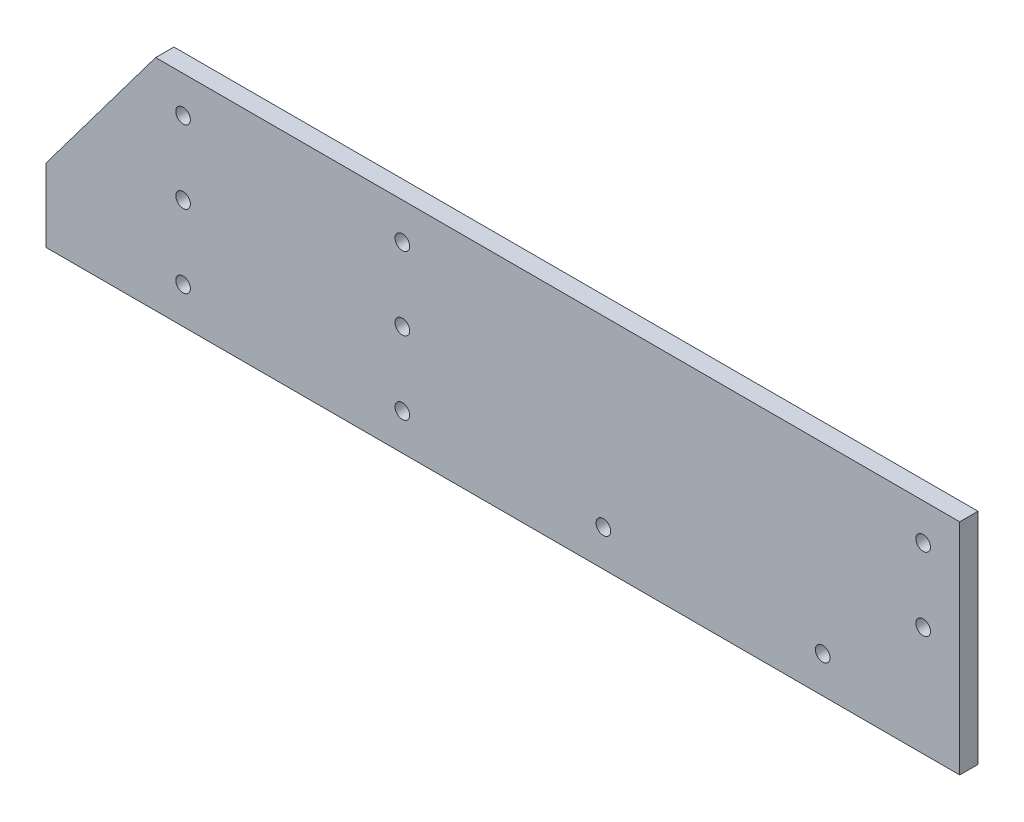
SolidWorks part; units mm, degrees
ref_plane "Front" through (0, 0, 0) normal (0, 0, 1) x (1, 0, 0)
ref_plane "Top" through (0, 0, 0) normal (0, 1, 0) x (1, 0, 0)
ref_plane "Right" through (0, 0, 0) normal (1, 0, 0) x (0, 0, -1)
sketch "Esquisse1" plane through (0, 0, 0) normal (0, 0, 1) x (1, 0, 0)
  line L1 (0, 0) -> (250, 0)
  line L2 (0, 0) -> (0, 60)
  line L3 (0, 60) -> (250, 60)
  line L4 (250, 0) -> (250, 60)
  dimension "D1" = 250
  dimension "D2" = 60
extrude "Boss.-Extru.1" add sketch "Esquisse1" along normal blind 5
sketch "Esquisse2" plane through (0, 0, 5) normal (0, 0, 1) x (1, 0, 0)
  line L0 (125, 0) -> (125, 60) construction
  line L1 (0, 0) -> (250, 0) construction
  line L2 (250, 60) -> (0, 60) construction
  line L3 (0, 10) -> (250, 10) construction
  line L4 (0, 60) -> (0, 0) construction
  line L5 (250, 0) -> (250, 60) construction
  line L6 (240, 60) -> (240, 50) construction
  line L7 (240, 50) -> (240, 30) construction
  line L8 (37.5, 10) -> (37.5, 60) construction
  line L9 (97.5, 10) -> (97.5, 60) construction
  line L10 (37.5, 35) -> (97.5, 35) construction
  line L11 (67.5, 35) -> (67.5, 60) construction
  circle A0 centre (37.5, 10) radius 2
  circle A1 centre (97.5, 10) radius 2
  circle A2 centre (152.5, 10) radius 2
  circle A3 centre (212.5, 10) radius 2
  circle A4 centre (240, 50) radius 2
  circle A5 centre (240, 30) radius 2
  circle A6 centre (37.5, 30) radius 2
  circle A7 centre (37.5, 50) radius 2
  circle A8 centre (97.5, 50) radius 2
  circle A9 centre (97.5, 30) radius 2
  dimension "D1" = 60
  dimension "D2" = 55
  dimension "D3" = 4
  dimension "D6" = 10
  dimension "D7" = 30
  dimension "D8" = 10
  dimension "D9" = 30
  dimension "D4" = 10
  dimension "D5" = 10
extrude "Enlèv. mat.-Extru.1" cut sketch "Esquisse2" against normal up to vertex (5 mm away)
sketch "Esquisse3" plane through (0, 0, 5) normal (0, 0, 1) x (1, 0, 0)
  line L0 (0, 20) -> (30, 60)
  line L1 (0, 60) -> (0, 0) construction
  line L2 (250, 60) -> (0, 60) construction
  line L3 (30, 60) -> (0, 60)
  line L4 (0, 60) -> (0, 20)
  dimension "D1" = 20
  dimension "D2" = 30
extrude "Enlèv. mat.-Extru.2" cut sketch "Esquisse3" against normal through all both and the other way through all
